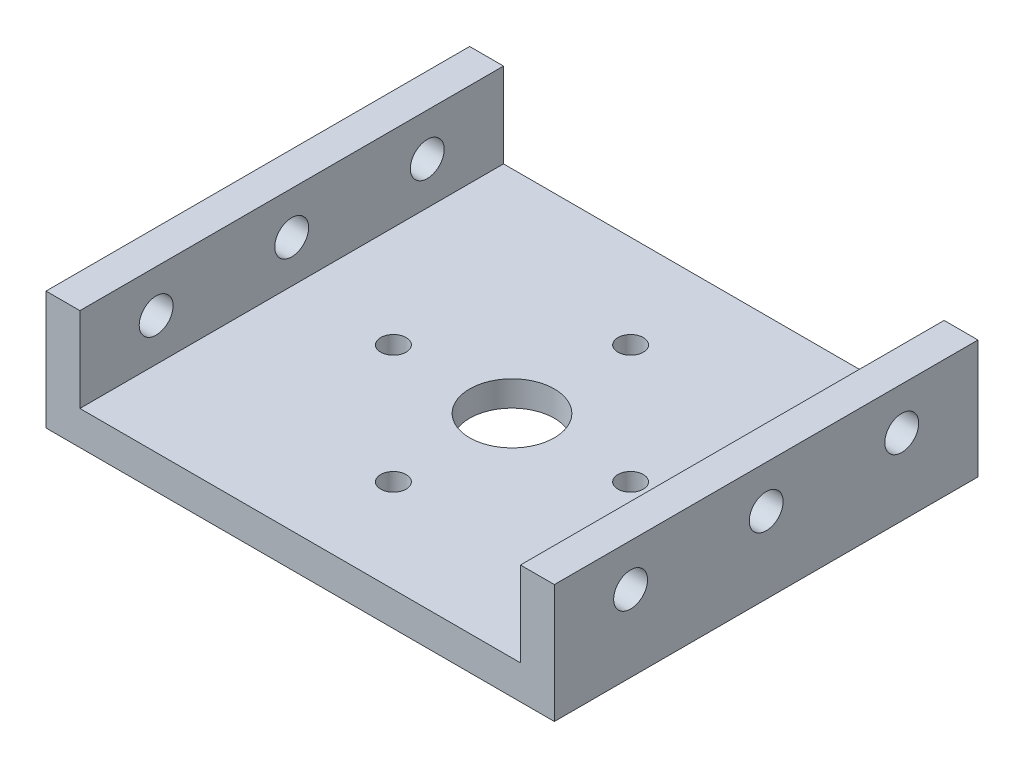
SolidWorks part; units mm, degrees
other "标注1"
sketch "草图5" plane through (30, 14, 25) normal (0.247, 0.8613, 0.4441) x (0.9392, -0.1, -0.3285)
material "6061 合金"
ref_plane "前视基准面" through (0, 0, 0) normal (0, 0, 1) x (1, 0, 0)
ref_plane "上视基准面" through (0, 0, 0) normal (0, 1, 0) x (1, 0, 0)
ref_plane "右视基准面" through (0, 0, 0) normal (1, 0, 0) x (0, 0, -1)
sketch "草图1" plane through (0, 0, 0) normal (0, 0, 1) x (1, 0, 0)
  line L0 (0, 47.6325) -> (0, -53.9266) construction
  line L1 (30, 0) -> (-30, 0)
  line L2 (-30, 0) -> (-30, 14)
  line L3 (-30, 14) -> (-26, 14)
  line L4 (-26, 14) -> (-26, 4)
  line L5 (-26, 4) -> (26, 4)
  line L7 (26, 14) -> (26, 4)
  line L8 (30, 14) -> (26, 14)
  line L9 (30, 0) -> (30, 14)
  point P10 (0, 4)
  point P11 (0, 0)
  dimension "D1" = 26
  dimension "D2" = 30
extrude "凸台-拉伸1" add sketch "草图1" along normal mid plane 50
sketch "草图2" plane through (30, 0, 0) normal (1, 0, 0) x (0, 0, -1)
  line L0 (-25, 0) -> (-25, 9) construction
  line L1 (-25, 0) -> (-25, 14) construction
  line L2 (0, 19.6652) -> (0, -8.571) construction
  line L3 (0, 9) -> (16, 9) construction
  line L4 (-25, 9) -> (-16, 9) construction
  line L5 (0, 9) -> (-16, 9) construction
  circle A4 centre (-16, 9) radius 2
  circle A8 centre (0, 9) radius 2
  circle A9 centre (16, 9) radius 2
  dimension "D2" = 16
  dimension "D3" = 16
  dimension "D1" = 9
sketch "草图3" plane through (0, 4, 0) normal (0, 1, 0) x (1, 0, 0)
  circle A0 centre (0, 0) radius 5
  circle A1 centre (0, 0) radius 14 construction
  circle A2 centre (0, 14) radius 1.5
  circle A3 centre (14, 0) radius 1.5
  circle A4 centre (0, -14) radius 1.5
  circle A5 centre (-14, 0) radius 1.5
  point P15 (0, 0)
  dimension "D1" = 4
extrude "切除-拉伸2" cut sketch "草图3" against normal up to surface (4 mm away) up to face at (0, 0, 0)
sketch "草图4" plane through (0, 0, 0) normal (0, -1, 0) x (1, 0, 0)
  circle A0 centre (0, 0) radius 14
extrude "切除-拉伸3" cut sketch "草图4" against normal blind 1
extrude "切除-拉伸4" cut sketch "草图2" against normal through all
